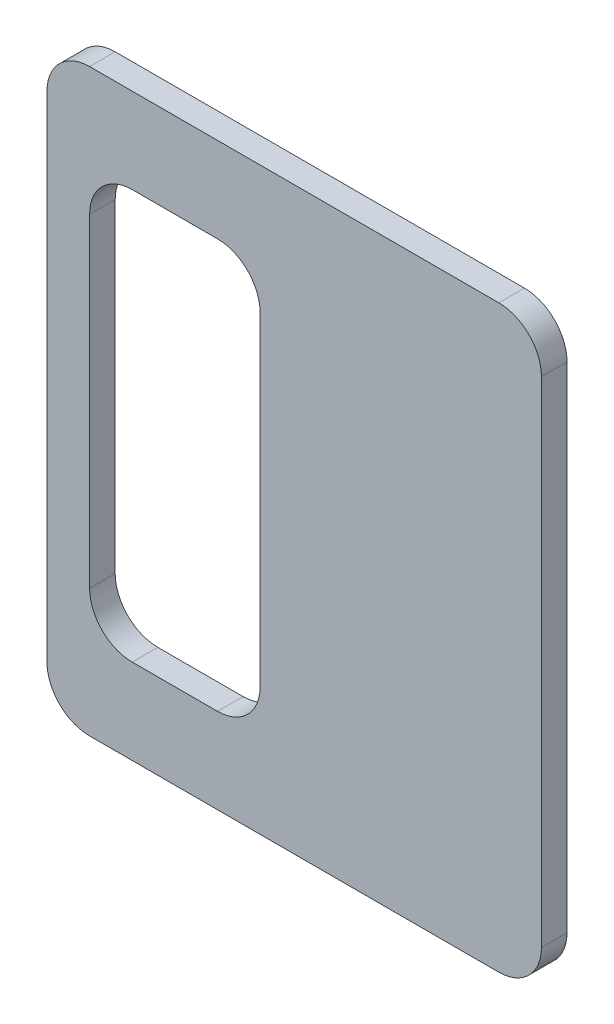
SolidWorks part; units mm, degrees
ref_plane "Front Plane" through (0, 0, 0) normal (0, 0, 1) x (1, 0, 0)
ref_plane "Top Plane" through (0, 0, 0) normal (0, 1, 0) x (1, 0, 0)
ref_plane "Right Plane" through (0, 0, 0) normal (1, 0, 0) x (0, 0, -1)
sketch "Sketch1" plane through (0, 0, 0) normal (0, 0, 1) x (1, 0, 0)
  line L1 (0, 0) -> (58, 0)
  line L2 (0, 0) -> (0, 68)
  line L3 (0, 68) -> (58, 68)
  line L4 (58, 0) -> (58, 68)
  line L5 (5, 58) -> (25, 58)
  line L6 (5, 58) -> (5, 10)
  line L7 (5, 10) -> (25, 10)
  line L8 (25, 58) -> (25, 10)
  dimension "D1" = 68
  dimension "D2" = 58
  dimension "D3" = 10
  dimension "D4" = 10
  dimension "D5" = 5
  dimension "D6" = 20
extrude "Boss-Extrude1" add sketch "Sketch1" along normal blind 3
fillet "Fillet2" radius 5 4 edges at (0, 0, 1.5) (0, 68, 1.5) (58, 68, 1.5) (58, 0, 1.5)
fillet "Fillet3" radius 5 4 edges at (25, 10, 1.5) (5, 10, 1.5) (5, 58, 1.5) (25, 58, 1.5)
